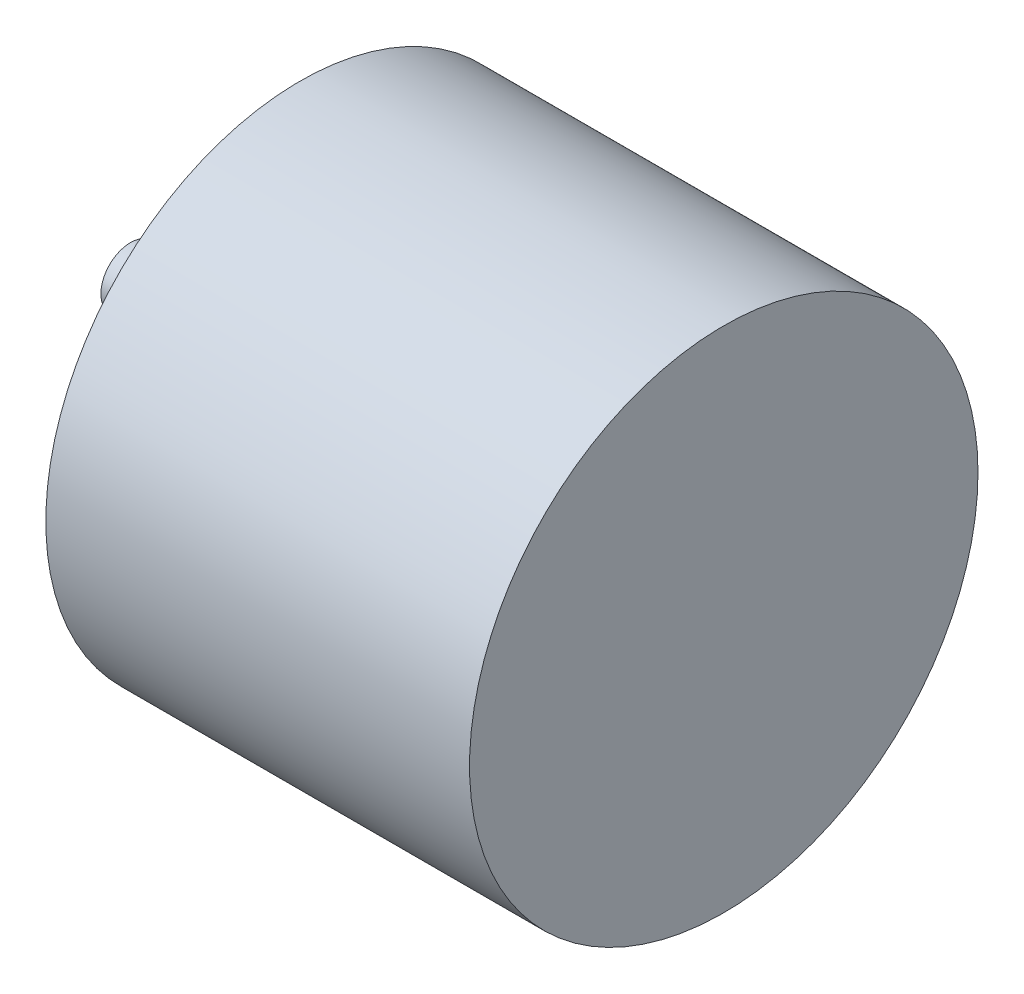
SolidWorks part; units mm, degrees
ref_plane "正面" through (0, 0, 0) normal (0, 0, 1) x (1, 0, 0)
ref_plane "平面" through (0, 0, 0) normal (0, 1, 0) x (1, 0, 0)
ref_plane "右側面" through (0, 0, 0) normal (1, 0, 0) x (0, 0, -1)
sketch "ｽｹｯﾁ1" plane through (0, 0, 0) normal (1, 0, 0) x (0, 0, -1)
  circle A0 centre (0, 0) radius 30
  dimension "D1" = 60
extrude "ﾎﾞｽ - 押し出し1" add sketch "ｽｹｯﾁ1" along normal blind 50
sketch "ｽｹｯﾁ2" plane through (0, 0, 0) normal (-1, 0, 0) x (0, 0, 1)
  circle A0 centre (0, 0) radius 3.5
  dimension "D1" = 7
extrude "ﾎﾞｽ - 押し出し2" add sketch "ｽｹｯﾁ2" along normal blind 20 contours A0
